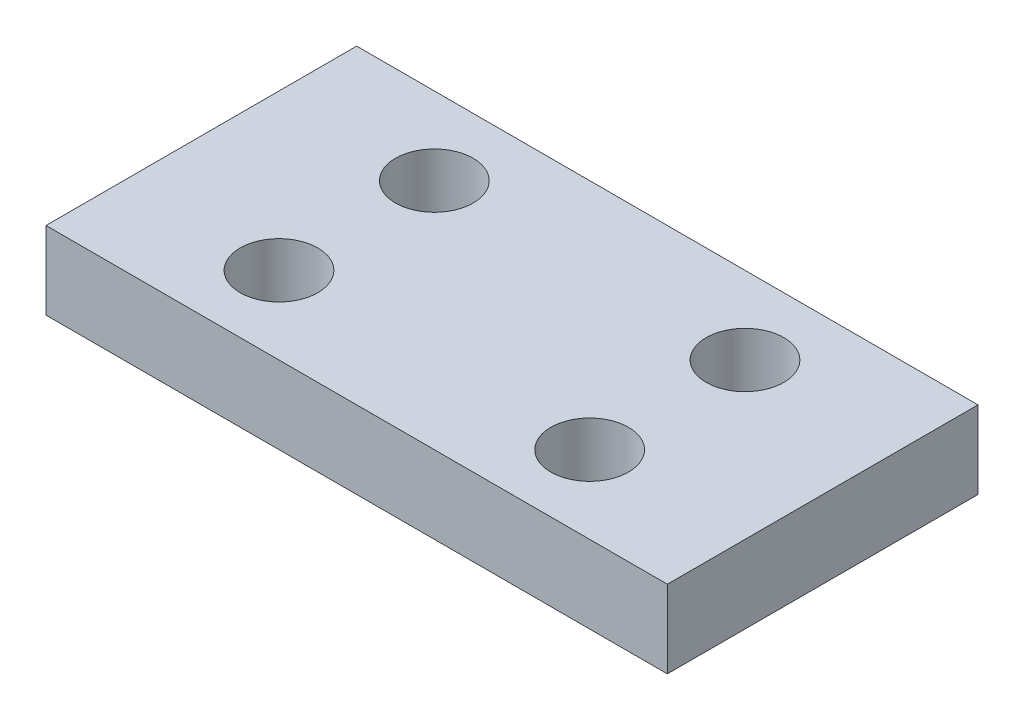
SolidWorks part; units mm, degrees
ref_plane "Front Plane" through (0, 0, 0) normal (0, 0, 1) x (1, 0, 0)
ref_plane "Top Plane" through (0, 0, 0) normal (0, 1, 0) x (1, 0, 0)
ref_plane "Right Plane" through (0, 0, 0) normal (1, 0, 0) x (0, 0, -1)
sketch "Sketch1" plane through (0, 0, 0) normal (0, 1, 0) x (1, 0, 0)
  line L0 (0, 0) -> (0, 9.2443) construction
  line L1 (-12.7, -6.35) -> (12.7, -6.35)
  line L2 (-12.7, -6.35) -> (-12.7, 6.35)
  line L3 (-12.7, 6.35) -> (12.7, 6.35)
  line L4 (12.7, -6.35) -> (12.7, 6.35)
  line L5 (-12.7, -6.35) -> (12.7, 6.35) construction
  line L6 (-12.7, 6.35) -> (12.7, -6.35) construction
  line L7 (0, 0) -> (15.5216, 0) construction
  circle A0 centre (6.35, 3.175) radius 1.5875
  circle A1 centre (-6.35, 3.175) radius 1.5875
  circle A2 centre (-6.35, -3.175) radius 1.5875
  circle A3 centre (6.35, -3.175) radius 1.5875
  point P0 (0, 0)
  dimension "D4" = 3.175
  dimension "D1" = 25.4
  dimension "D2" = 12.7
  dimension "D3" = 6.35
extrude "Boss-Extrude1" add sketch "Sketch1" along normal blind 3.175
